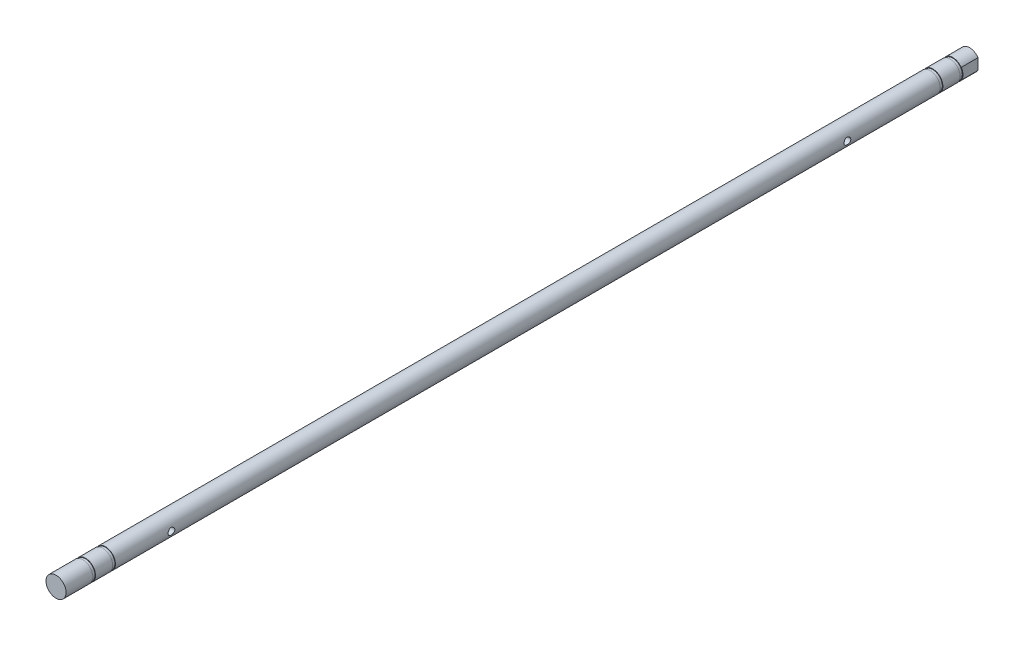
SolidWorks part; units mm, degrees
material "AISI 4340 Steel, normalized"
ref_plane "Front Plane" through (0, 0, 0) normal (0, 0, 1) x (1, 0, 0)
ref_plane "Top Plane" through (0, 0, 0) normal (0, 1, 0) x (1, 0, 0)
ref_plane "Right Plane" through (0, 0, 0) normal (1, 0, 0) x (0, 0, -1)
sketch "Sketch1" plane through (0, 0, 0) normal (0, 0, 1) x (1, 0, 0)
  circle A0 centre (0, 0) radius 3
extrude "Boss-Extrude1" add sketch "Sketch1" along normal blind 275
sketch "Sketch3" plane through (0, 0, 0) normal (1, 0, 0) x (0, 0, -1)
  line L0 (0, 3) -> (-275, 3) construction
  line L1 (-267, 3) -> (-266.2, 3)
  line L2 (-267, 3) -> (-267, 2.5)
  line L3 (-267, 2.5) -> (-266.2, 2.5)
  line L4 (-266.2, 3) -> (-266.2, 2.5)
  line L5 (-275, 3) -> (-275, -3) construction
  line L6 (-263.365, 0) -> (-260, 0) construction
  line L7 (-261.05, 3) -> (-260.25, 3)
  line L8 (-261.05, 3) -> (-261.05, 2.5)
  line L9 (-261.05, 2.5) -> (-260.25, 2.5)
  line L10 (-260.25, 3) -> (-260.25, 2.5)
  line L11 (-13.8, 3) -> (-13, 3)
  line L12 (-13.8, 3) -> (-13.8, 2.5)
  line L13 (-13.8, 2.5) -> (-13, 2.5)
  line L14 (-13, 3) -> (-13, 2.5)
  line L15 (-7.85, 3) -> (-7.05, 3)
  line L16 (-7.85, 3) -> (-7.85, 2.5)
  line L17 (-7.85, 2.5) -> (-7.05, 2.5)
  line L18 (-7.05, 3) -> (-7.05, 2.5)
  point P12 (-260.65, 2.5)
  point P21 (-7.05, 2.75)
  dimension "D1" = 0.8
  dimension "D2" = 0.5
  dimension "D3" = 8
  dimension "D4" = 0.5
  dimension "D5" = 0.8
  dimension "D6" = 13.95
  dimension "D7" = 5.15
  dimension "D8" = 0.5
  dimension "D9" = 0.8
  dimension "D10" = 0.5
  dimension "D11" = 0.8
  dimension "D12" = 5.15
  dimension "D13" = 261.2
revolve "Cut-Revolve1" cut sketch "Sketch3" angle 360 about L6
sketch "Sketch4" plane through (0, 0, 0) normal (0, 1, 0) x (1, 0, 0)
  line L0 (0, 6.9099) -> (0, -272.7358) construction
  line L1 (3, 0) -> (-3, 0) construction
  line L2 (2.5, 0) -> (5.9701, 0)
  line L3 (2.5, 0) -> (2.5, -7)
  line L4 (2.5, -7) -> (5.9701, -7)
  line L5 (5.9701, 0) -> (5.9701, -7)
  line L6 (-5.4253, 0) -> (-2.5, 0)
  line L7 (-5.4253, 0) -> (-5.4253, -7)
  line L8 (-5.4253, -7) -> (-2.5, -7)
  line L9 (-2.5, 0) -> (-2.5, -7)
  line L10 (3, -7.05) -> (3, 0) construction
  line L11 (-3, 0) -> (-3, -7.05) construction
  dimension "D1" = 7
  dimension "D2" = 0.5
  dimension "D3" = 0.5
extrude "Cut-Extrude2" cut sketch "Sketch4" against normal through all both and the other way through all
chamfer "Chamfer1" distance 0.3 angle 45 2 edges at (0, -3, 0) (0, 3, 0)
sketch "Sketch5" plane through (0, 0, 0) normal (0, 0, 1) x (1, 0, 0)
  circle A0 centre (0, 0) radius 2.85
  circle A1 centre (0, 0) radius 2.49
extrude "Retaining_Grooves_D5p7_1" add sketch "Sketch5" along normal blind 0.8 from offset 7.05
sketch "Sketch6" plane through (0, 0, 0) normal (0, 0, 1) x (1, 0, 0)
  circle A0 centre (0, 0) radius 2.85
  circle A1 centre (0, 0) radius 2.49
extrude "Retaining_Grooves_D5p7_2" add sketch "Sketch6" along normal blind 0.8 from offset 13
sketch "Sketch7" plane through (0, 0, 0) normal (0, 0, 1) x (1, 0, 0)
  circle A0 centre (0, 0) radius 2.85
  circle A1 centre (0, 0) radius 2.49
extrude "Retaining_Grooves_D5p7_3" add sketch "Sketch7" along normal blind 0.8 from offset 260.25
sketch "Sketch8" plane through (0, 0, 0) normal (0, 0, 1) x (1, 0, 0)
  circle A0 centre (0, 0) radius 2.85
  circle A1 centre (0, 0) radius 2.49
extrude "Retaining_Grooves_D5p7_4" add sketch "Sketch8" along normal blind 0.8 from offset 266.2
sketch "Sketch9" plane through (0, 0, 0) normal (1, 0, 0) x (0, 0, -1)
  circle A0 centre (-41.5, 0) radius 1
  circle A1 centre (-243.5, 0) radius 1
extrude "Two_Hub_Cross_Pin_D2" cut sketch "Sketch9" against normal through all and the other way through all
sketch "Sketch10" plane through (0, 0, 0) normal (0, 0, -1) x (-1, 0, 0)
  circle A0 centre (0, 0) radius 3.1
extrude "RevB_Lower_Shaft_Nose_Clearance_2mm" cut sketch "Sketch10" against normal blind 2
